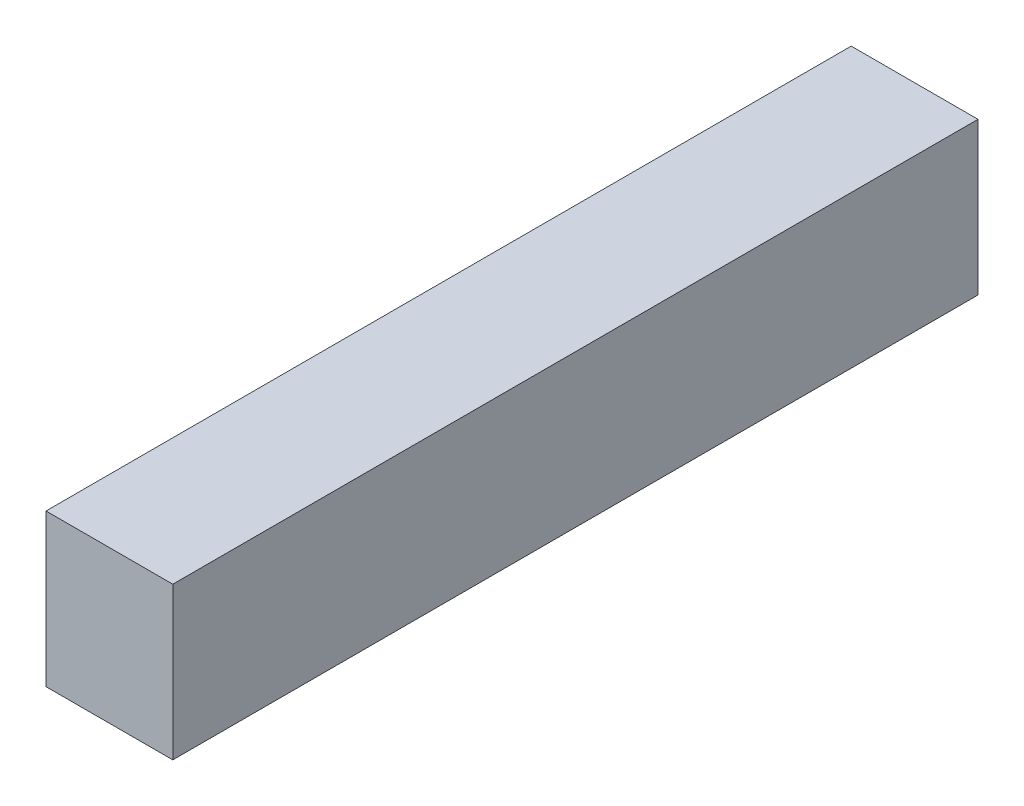
SolidWorks part; units mm, degrees
ref_plane "Front Plane" through (0, 0, 0) normal (0, 0, 1) x (1, 0, 0)
ref_plane "Top Plane" through (0, 0, 0) normal (0, 1, 0) x (1, 0, 0)
ref_plane "Right Plane" through (0, 0, 0) normal (1, 0, 0) x (0, 0, -1)
sketch "Sketch1" plane through (0, 0, 0) normal (0, 0, 1) x (1, 0, 0)
  line L1 (-1, 1.2) -> (1, 1.2)
  line L2 (-1, 1.2) -> (-1, -1.2)
  line L3 (-1, -1.2) -> (1, -1.2)
  line L4 (1, 1.2) -> (1, -1.2)
  line L5 (-1, 1.2) -> (1, -1.2) construction
  line L6 (-1, -1.2) -> (1, 1.2) construction
  point P0 (0, 0)
  point P6 (0, 0)
  dimension "D1" = 2
  dimension "D2" = 2.4
extrude "Boss-Extrude1" add sketch "Sketch1" along normal blind 12.7 contours L4 L3 L2 L1
